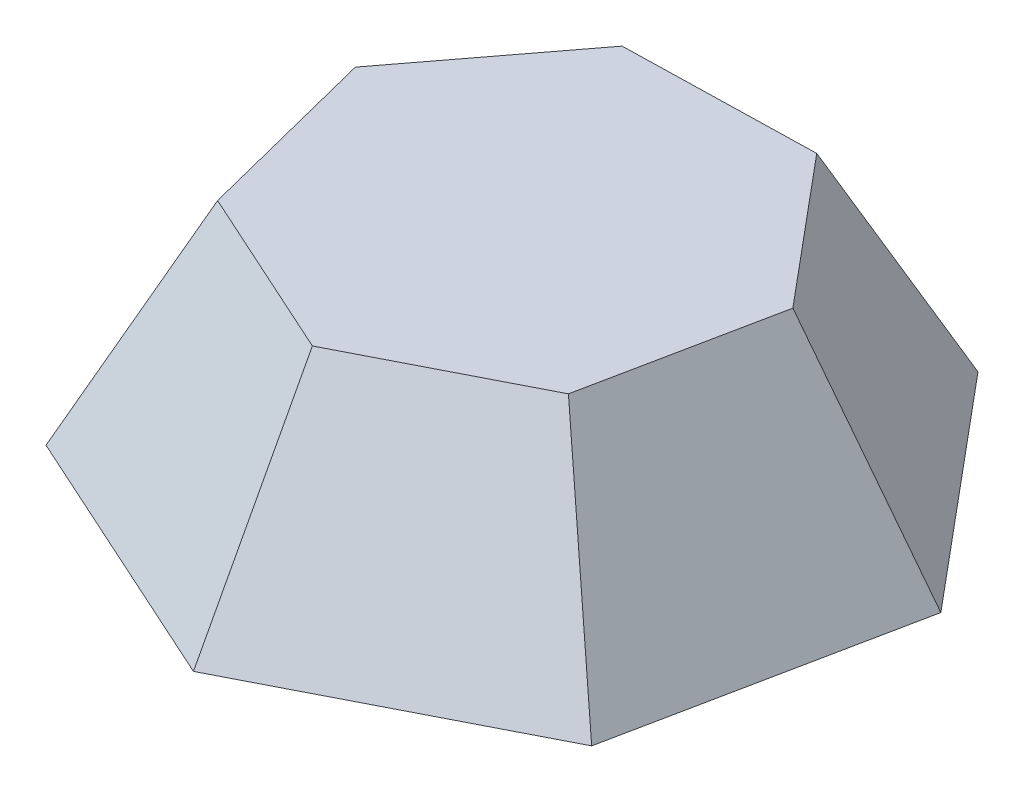
SolidWorks part; units mm, degrees
ref_plane "Front" through (0, 0, 0) normal (0, 0, 1) x (1, 0, 0)
ref_plane "Top" through (0, 0, 0) normal (0, 1, 0) x (1, 0, 0)
ref_plane "Right" through (0, 0, 0) normal (1, 0, 0) x (0, 0, -1)
sketch "Sketch1" plane through (0, 0, 0) normal (0, 1, 0) x (1, 0, 0)
  line L1 (7.9531, -6.0443) -> (9.6843, 2.4494)
  line L2 (9.6843, 2.4494) -> (4.1231, 9.0986)
  line L3 (4.1231, 9.0986) -> (-4.5429, 8.8965)
  line L4 (-4.5429, 8.8965) -> (-9.788, 1.995)
  line L5 (-9.788, 1.995) -> (-7.6625, -6.4087)
  line L6 (-7.6625, -6.4087) -> (0.233, -9.9865)
  line L7 (0.233, -9.9865) -> (7.9531, -6.0443)
  circle A0 centre (0, 0) radius 9 construction
ref_plane "Plane1" through (0, -10, 0) normal (0, 1, 0) x (1, 0, 0)
sketch "Sketch2" plane through (0, -10, 0) normal (0, 1, 0) x (1, 0, 0)
  line L14 (6.4136, 14.1535) -> (-7.0668, 13.8389)
  line L15 (15.0645, 3.8101) -> (6.4136, 14.1535)
  line L16 (12.3714, -9.4023) -> (15.0645, 3.8101)
  line L17 (0.3625, -15.5346) -> (12.3714, -9.4023)
  line L18 (-11.9195, -9.969) -> (0.3625, -15.5346)
  line L19 (-15.2258, 3.1034) -> (-11.9195, -9.969)
  line L20 (-7.0668, 13.8389) -> (-15.2258, 3.1034)
  line L21 (6.4136, 14.1535) -> (-7.0668, 13.8389)
  line L22 (15.0645, 3.8101) -> (6.4136, 14.1535)
  line L23 (12.3714, -9.4023) -> (15.0645, 3.8101)
  line L24 (0.3625, -15.5346) -> (12.3714, -9.4023)
  line L25 (-11.9195, -9.969) -> (0.3625, -15.5346)
  line L26 (-15.2258, 3.1034) -> (-11.9195, -9.969)
  line L27 (-7.0668, 13.8389) -> (-15.2258, 3.1034)
  dimension "D1" = 5
loft "Loft1" add profiles "Sketch2", "Sketch1"
sketch "Sketch3" plane through (0, -10, 0) normal (0, -1, 0) x (1, 0, 0)
  circle A0 centre (0, 0) radius 1.5
extrude "Cut-Extrude1" cut sketch "Sketch3" against normal blind 7
